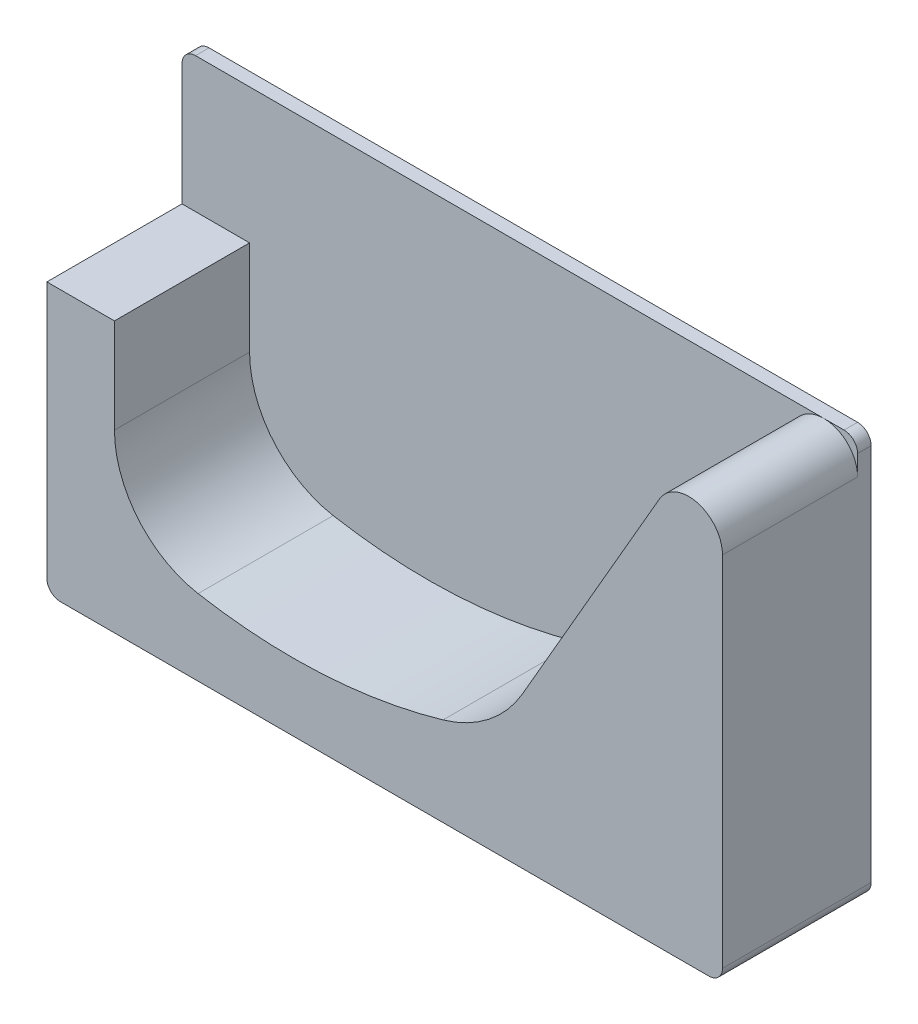
SolidWorks part; units mm, degrees
ref_plane "Alzado" through (0, 0, 0) normal (0, 0, 1) x (1, 0, 0)
ref_plane "Planta" through (0, 0, 0) normal (0, 1, 0) x (1, 0, 0)
ref_plane "Vista lateral" through (0, 0, 0) normal (1, 0, 0) x (0, 0, -1)
sketch "Croquis1" plane through (0, 0, 0) normal (0, 0, 1) x (1, 0, 0)
  line L1 (0, 0) -> (100, 0)
  line L2 (0, 0) -> (0, 60)
  line L3 (0, 60) -> (100, 60)
  line L4 (100, 0) -> (100, 60)
  point P5 (0, 0)
  dimension "D1" = 100
  dimension "D2" = 60
extrude "Saliente-Extruir1" add sketch "Croquis1" along normal blind 2
fillet "Redondeo1" radius 2 4 edges at (0, 0, 1) (100, 0, 1) (100, 60, 1) (0, 60, 1)
sketch "Croquis2" plane through (0, 0, 2) normal (0, 0, 1) x (1, 0, 0)
  line L1 (98, 60) -> (2, 60) construction
  line L2 (70.3901, 22.3743) -> (90.6699, 57.5)
  line L3 (100, 2) -> (100, 58) construction
  line L5 (100, 55) -> (100, 2)
  line L6 (98, 0) -> (2, 0)
  line L7 (0, 2) -> (0, 40)
  line L9 (0, 40) -> (10, 40)
  line L10 (10, 40) -> (10, 26)
  line L11 (4.8061, 10) -> (104.1451, 10) construction
  arc A2 (90.6699, 57.5) -> (100, 55) centre (95, 55) cw
  arc A3 (100, 2) -> (98, 0) centre (98, 2) cw
  arc A4 (2, 0) -> (0, 2) centre (2, 2) cw
  arc A5 (0, 2) -> (2, 0) centre (2, 2) ccw construction
  arc A7 (10, 26) -> (22.379, 11.2308) centre (25, 26) ccw
  arc A8 (22.379, 11.2308) -> (58.6401, 13.1658) centre (36.3578, 90) ccw
  arc A9 (58.6401, 13.1658) -> (70.3901, 22.3743) centre (53.0695, 32.3743) ccw
  point P0 (0, 58)
  point P37 (21.3004, 12.4714)
  dimension "D3" = 5
  dimension "D4" = 15
  dimension "D5" = 80
  dimension "D8" = 20
  dimension "D1" = 30
  dimension "D6" = 10
  dimension "D7" = 20
  dimension "D9" = 10
  dimension "D10" = 14
extrude "Saliente-Extruir2" add sketch "Croquis2" along normal blind 20
